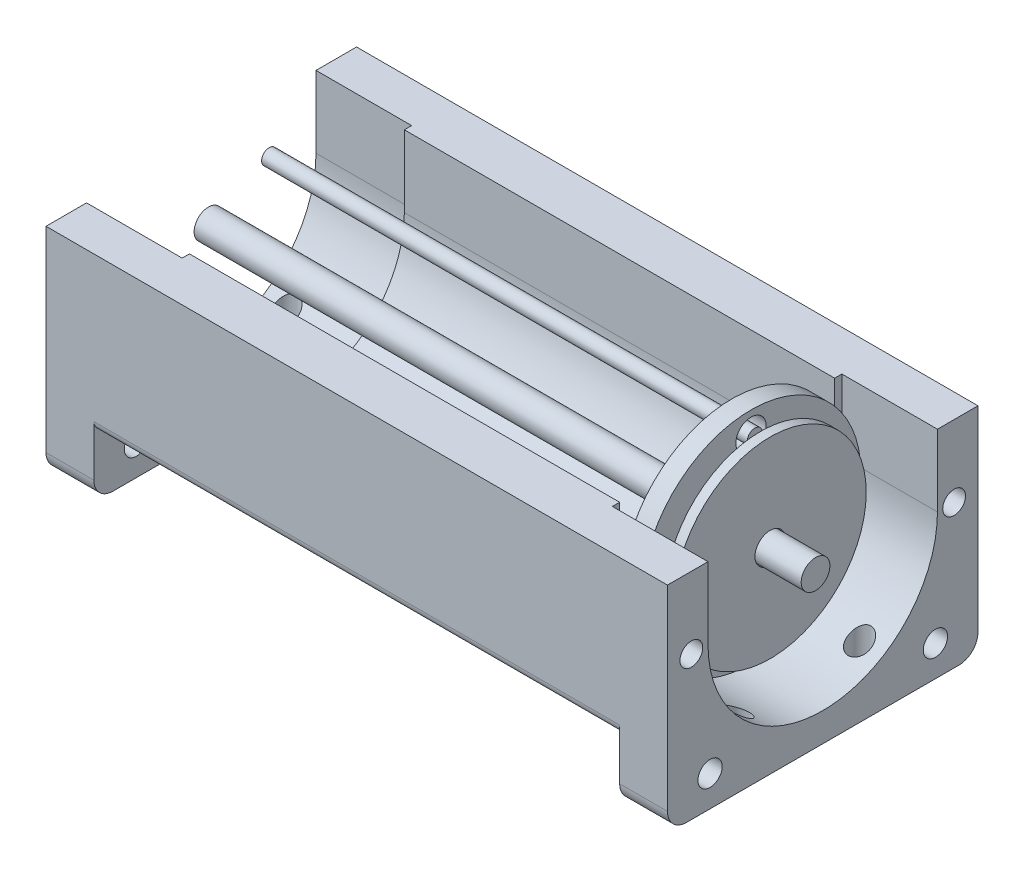
SolidWorks part; units mm, degrees
ref_plane "Front Plane" through (0, 0, 0) normal (0, 0, 1) x (1, 0, 0)
ref_plane "Top Plane" through (0, 0, 0) normal (0, 1, 0) x (1, 0, 0)
ref_plane "Right Plane" through (0, 0, 0) normal (1, 0, 0) x (0, 0, -1)
sketch "Sketch1" plane through (0, 0, 0) normal (1, 0, 0) x (0, 0, -1)
  line L0 (-22.4812, 0) -> (-22.4812, 15)
  line L1 (22.4812, 0) -> (22.4812, 15)
  line L2 (-23.3122, -17.371) -> (-30.4812, -17.371)
  line L3 (0, 0) -> (0, 31.7138) construction
  line L4 (-15.3123, -30) -> (15.4297, -30)
  line L5 (-17.3123, -23.371) -> (-17.3123, -28)
  line L6 (17.4297, -23.371) -> (17.4297, -28)
  line L7 (23.4297, -17.371) -> (30.0587, -17.371)
  line L8 (-32.4812, 15) -> (-32.4812, -15.371)
  line L9 (22.4812, 15) -> (32.4812, 15)
  line L10 (-22.4812, 15) -> (-32.4812, 15)
  line L11 (32.4812, 15) -> (32.4813, -15.371)
  line L13 (30.4812, -17.371) -> (30.0587, -17.371)
  line L14 (-27.4812, 15) -> (-27.4813, 0) construction
  line L15 (27.4812, 15) -> (27.4812, 0) construction
  arc A0 (-22.4812, 0) -> (22.4812, 0) centre (0, 0) ccw
  arc A1 (-23.3122, -17.371) -> (-17.3123, -23.371) centre (-23.3122, -23.371) cw
  arc A2 (17.4297, -23.371) -> (23.4297, -17.371) centre (23.4297, -23.371) cw
  arc A3 (-30.4812, -17.371) -> (-32.4812, -15.371) centre (-30.4812, -15.371) cw
  arc A4 (32.4813, -15.371) -> (30.4812, -17.371) centre (30.4812, -15.371) cw
  arc A5 (-17.3123, -28) -> (-15.3123, -30) centre (-15.3123, -28) ccw
  arc A6 (17.4297, -28) -> (15.4297, -30) centre (15.4297, -28) cw
  circle A7 centre (0, 0) radius 27.4813 construction
  circle A8 centre (-27.4813, 0) radius 2.3813
  circle A9 centre (27.4812, 0) radius 2.3813
  dimension "D1" = 6
  dimension "D2" = 6
  dimension "D3" = 2
  dimension "D4" = 2
  dimension "D5" = 2
  dimension "D6" = 10
  dimension "D7" = 54.9625
  dimension "D8" = 4.7625
extrude "Boss-Extrude1" add sketch "Sketch1" along normal mid plane 90
ref_plane "Plane1" through (45, 0, 0) normal (1, 0, 0) x (0, 0, -1)
ref_plane "Plane2" through (46, 0, 0) normal (1, 0, 0) x (0, 0, -1)
sketch "Sketch3" plane through (46, 0, 0) normal (1, 0, 0) x (0, 0, -1)
  line L0 (0, 0) -> (0, 1.0694) construction
  circle A0 centre (0, 0) radius 3.175
  circle A1 centre (0, 18.5125) radius 1.5875 construction
  circle A2 centre (0, 18.5125) radius 3.175
  circle A3 centre (0, 0) radius 23
  circle A4 centre (-18.5125, 0) radius 1.5875 construction
  circle A5 centre (-18.5125, 0) radius 3.175
  circle A6 centre (0, -18.5125) radius 1.5875 construction
  circle A7 centre (0, -18.5125) radius 3.175
  circle A8 centre (18.5125, 0) radius 1.5875 construction
  circle A9 centre (18.5125, 0) radius 3.175
  circle A10 centre (0, 0) radius 20.1 construction
  circle A11 centre (0, 0) radius 18.5125 construction
  dimension "D1" = 6.35
  dimension "D2" = 3.175
  dimension "D3" = 6.35
  dimension "D4" = 46
  dimension "D5" = 40.2
  dimension "D6" = 37.025
extrude "Boss-Extrude2" add sketch "Sketch3" along normal blind 4 separate body
ref_plane "Sketch16" through (52, 0, 0) normal (1, 0, 0) x (0, 0, -1)
sketch "Sketch17" plane through (52, 0, 0) normal (1, 0, 0) x (0, 0, -1)
  circle A1 centre (0, 0) radius 3.175
  circle A2 centre (0, 0) radius 20.1
  dimension "D1" = 6.35
extrude "Boss-Extrude4" add sketch "Sketch17" along normal blind 2 separate body
sketch "Sketch19" plane through (0, 0, 0) normal (1, 0, 0) x (0, 0, -1)
  circle A0 centre (0, 0) radius 3
  circle A1 centre (0, 0) radius 18.5125 construction
  dimension "D1" = 37.025
  dimension "D2" = 6
extrude "Boss-Extrude6" add sketch "Sketch19" along normal mid plane 127
sketch "Sketch20" plane through (0, 0, 0) normal (1, 0, 0) x (0, 0, -1)
  circle A0 centre (0, 0) radius 18.5125 construction
  circle A1 centre (0, 18.5125) radius 1.5875
  circle A2 centre (18.5125, 0) radius 1.5875
  circle A3 centre (0, -18.5125) radius 1.5875
  circle A4 centre (-18.5125, 0) radius 1.5875
  dimension "D1" = 37.025
  dimension "D2" = 3.175
extrude "Boss-Extrude7" add sketch "Sketch20" along normal mid plane 101.6 separate body
sketch "Sketch21" plane through (45, 0, 0) normal (1, 0, 0) x (0, 0, -1)
  line L0 (-24, 0) -> (-24, 15)
  line L1 (24, 0) -> (24, 15)
  line L2 (-23.3122, -17.371) -> (-30.4812, -17.371)
  line L3 (0, 0) -> (0, 31.7138) construction
  line L4 (-15.3123, -30) -> (15.4297, -30)
  line L5 (-17.3123, -23.371) -> (-17.3123, -28)
  line L6 (17.4297, -23.371) -> (17.4297, -28)
  line L7 (23.4297, -17.371) -> (30.0587, -17.371)
  line L8 (-32.4812, 15) -> (-32.4812, -15.371)
  line L9 (24, 15) -> (32.4812, 15)
  line L10 (-24, 15) -> (-32.4812, 15)
  line L11 (32.4812, 15) -> (32.4813, -15.371)
  line L12 (-24, 0) -> (24, 0) construction
  line L13 (30.4812, -17.371) -> (30.0587, -17.371)
  line L14 (0, 0) -> (0, -24) construction
  arc A0 (-24, 0) -> (24, 0) centre (0, 0) ccw
  arc A1 (-23.3122, -17.371) -> (-17.3123, -23.371) centre (-23.3122, -23.371) cw
  arc A2 (17.4297, -23.371) -> (23.4297, -17.371) centre (23.4297, -23.371) cw
  arc A3 (-30.4812, -17.371) -> (-32.4812, -15.371) centre (-30.4812, -15.371) cw
  arc A4 (32.4813, -15.371) -> (30.4812, -17.371) centre (30.4812, -15.371) cw
  arc A5 (-17.3123, -28) -> (-15.3123, -30) centre (-15.3123, -28) ccw
  arc A6 (17.4297, -28) -> (15.4297, -30) centre (15.4297, -28) cw
  circle A7 centre (0, 0) radius 23 construction
  circle A8 centre (0, 0) radius 27.4812 construction
  circle A9 centre (-27.4813, 0) radius 2.3813
  circle A10 centre (27.4812, 0) radius 2.3812
  dimension "D1" = 6
  dimension "D2" = 6
  dimension "D3" = 2
  dimension "D4" = 2
  dimension "D5" = 2
  dimension "D6" = 54.9625
  dimension "D7" = 46
extrude "Boss-Extrude8" add sketch "Sketch21" along normal blind 10
ref_plane "Plane5" through (55, 0, 0) normal (1, 0, 0) x (0, 0, -1)
sketch "Sketch23" plane through (55, 0, 0) normal (1, 0, 0) x (0, 0, -1)
  line L0 (-24, 0) -> (-24, 15)
  line L1 (24, 0) -> (24, 15)
  line L2 (32.4812, 15) -> (24, 15)
  line L4 (-28.4812, -30) -> (28.4812, -30)
  line L8 (-32.4812, 15) -> (-32.4813, -26)
  line L10 (-24, 15) -> (-32.4812, 15)
  line L11 (32.4812, 15) -> (32.4813, -26)
  arc A0 (-24, 0) -> (24, 0) centre (0, 0) ccw
  arc A1 (28.4812, -30) -> (32.4813, -26) centre (28.4813, -26) ccw
  circle A2 centre (0, 0) radius 23.5712 construction
  arc A3 (-28.4812, -30) -> (-32.4813, -26) centre (-28.4813, -26) cw
  circle A4 centre (-23.5712, -23.5712) radius 2.54
  circle A5 centre (23.5712, -23.5712) radius 2.54
  circle A7 centre (-27.4813, 0) radius 2.3813
  circle A8 centre (27.4812, 0) radius 2.3812
  circle A9 centre (0, 0) radius 22.4812 construction
  dimension "D1" = 47.1424
  dimension "D2" = 4
  dimension "D3" = 4
  dimension "D7" = 44.9625
extrude "Boss-Extrude9" add sketch "Sketch23" along normal blind 10
ref_plane "Plane6" through (0, -30, 0) normal (0, -1, 0) x (1, 0, 0)
sketch "Sketch24" plane through (0, -30, 0) normal (0, -1, 0) x (1, 0, 0)
  line L0 (55, 0) -> (65, 0) construction
  line L1 (55, -24.75) -> (55, 24.75) construction
  line L2 (65, 28.4812) -> (65, -28.4812) construction
  line L3 (60, 12.7) -> (60, -12.7) construction
  circle A0 centre (60, 0) radius 12.7 construction
  circle A1 centre (60, 12.7) radius 2.3812
  circle A2 centre (60, -12.7) radius 2.3812
  dimension "D1" = 25.4
  dimension "D2" = 4.7625
extrude "Cut-Extrude1" cut sketch "Sketch24" against normal blind 50 contours A2 | A1
ref_plane "Plane7" through (-45, 0, 0) normal (-1, 0, 0) x (0, 0, 1)
sketch "Sketch25" plane through (-45, 0, 0) normal (-1, 0, 0) x (0, 0, 1)
  line L0 (-24, 0) -> (-24, 15)
  line L1 (24, 0) -> (24, 15)
  line L2 (-23.3122, -17.371) -> (-30.4812, -17.371)
  line L3 (0, 0) -> (0, 31.7138) construction
  line L4 (-15.3123, -30) -> (15.4297, -30)
  line L5 (-17.3123, -23.371) -> (-17.3123, -28)
  line L6 (17.4297, -23.371) -> (17.4297, -28)
  line L7 (23.4297, -17.371) -> (30.0587, -17.371)
  line L8 (-32.4812, 15) -> (-32.4812, -15.371)
  line L9 (24, 15) -> (32.4812, 15)
  line L10 (-24, 15) -> (-32.4812, 15)
  line L11 (32.4812, 15) -> (32.4813, -15.371)
  line L12 (-24, 0) -> (24, 0) construction
  line L13 (30.4812, -17.371) -> (30.0587, -17.371)
  line L14 (0, 0) -> (0, -24) construction
  arc A0 (-24, 0) -> (24, 0) centre (0, 0) ccw
  arc A1 (-23.3122, -17.371) -> (-17.3123, -23.371) centre (-23.3122, -23.371) cw
  arc A2 (17.4297, -23.371) -> (23.4297, -17.371) centre (23.4297, -23.371) cw
  arc A3 (-30.4812, -17.371) -> (-32.4812, -15.371) centre (-30.4812, -15.371) cw
  arc A4 (32.4813, -15.371) -> (30.4812, -17.371) centre (30.4812, -15.371) cw
  arc A5 (-17.3123, -28) -> (-15.3123, -30) centre (-15.3123, -28) ccw
  arc A6 (17.4297, -28) -> (15.4297, -30) centre (15.4297, -28) cw
  circle A7 centre (0, 0) radius 23 construction
  circle A8 centre (-27.4812, 0) radius 2.3813
  circle A9 centre (27.4813, 0) radius 2.3813
  dimension "D1" = 6
  dimension "D2" = 6
  dimension "D3" = 2
  dimension "D4" = 2
  dimension "D5" = 2
  dimension "D7" = 46
extrude "Boss-Extrude10" add sketch "Sketch25" along normal blind 10
ref_plane "Plane8" through (-55, 0, 0) normal (-1, 0, 0) x (0, 0, 1)
sketch "Sketch27" plane through (-55, 0, 0) normal (-1, 0, 0) x (0, 0, 1)
  line L0 (-24, 0) -> (-24, 15)
  line L1 (24, 0) -> (24, 15)
  line L3 (0, 0) -> (0, 31.7138) construction
  line L4 (-28.4812, -30) -> (28.4812, -30)
  line L8 (-32.4812, 15) -> (-32.4813, -26)
  line L9 (24, 15) -> (32.4812, 15)
  line L10 (-24, 15) -> (-32.4812, 15)
  line L11 (32.4812, 15) -> (32.4813, -26)
  arc A0 (-24, 0) -> (24, 0) centre (0, 0) ccw
  arc A1 (-32.4813, -26) -> (-28.4812, -30) centre (-28.4813, -26) ccw
  arc A2 (28.4812, -30) -> (32.4813, -26) centre (28.4813, -26) ccw
  circle A3 centre (0, 0) radius 23.5712 construction
  circle A4 centre (-23.5712, -23.5712) radius 2.54
  circle A5 centre (23.5712, -23.5712) radius 2.54
  circle A7 centre (-27.4812, 0) radius 2.3813
  circle A8 centre (27.4813, 0) radius 2.3813
  dimension "D1" = 4
  dimension "D2" = 4
  dimension "D3" = 47.1424
extrude "Boss-Extrude11" add sketch "Sketch27" along normal blind 10
mirror "Mirror6" about plane through (0, 0, 0) normal (1, 0, 0) of "Cut-Extrude1"
